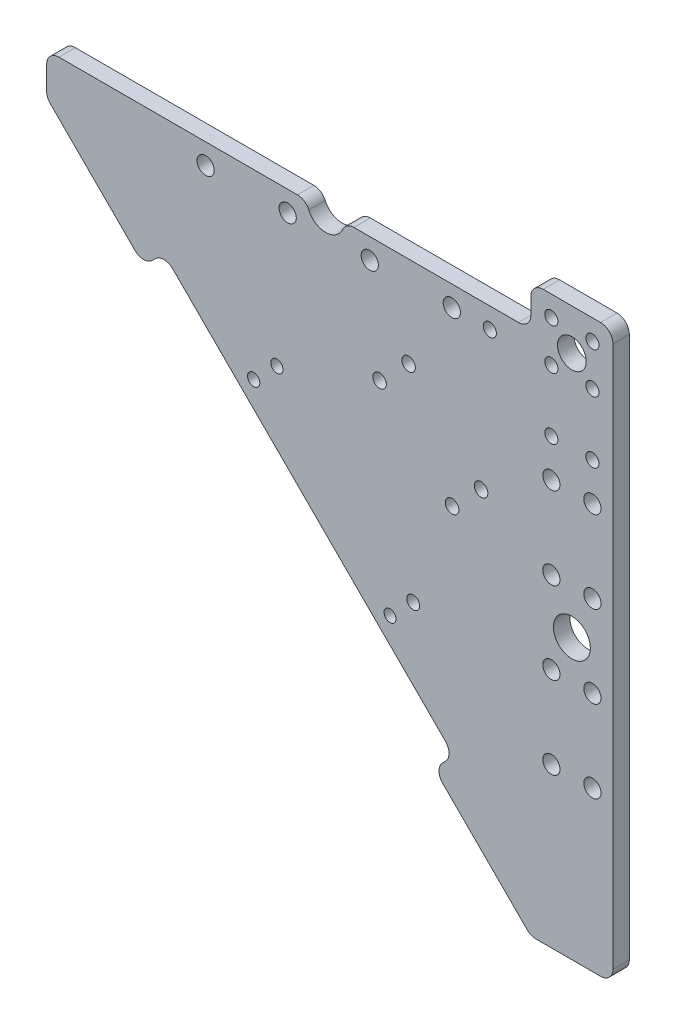
SolidWorks part; units mm, degrees
material "Thornel Mat VMA"
ref_plane "前视基准面" through (0, 0, 0) normal (0, 0, 1) x (1, 0, 0)
ref_plane "上视基准面" through (0, 0, 0) normal (0, 1, 0) x (1, 0, 0)
ref_plane "右视基准面" through (0, 0, 0) normal (1, 0, 0) x (0, 0, -1)
other "Configuration Table"
sketch "草图1" plane through (0, 0, 0) normal (0, 0, 1) x (1, 0, 0)
  line L0 (-128, -10) -> (-10, -128)
  line L5 (-10, 10) -> (10, 10)
  line L6 (-10, 10) -> (-10, -10)
  line L11 (-10, -10) -> (10, -10)
  line L12 (10, 10) -> (10, -10)
  line L13 (-10, 10) -> (10, -10) construction
  line L14 (-10, -10) -> (10, 10) construction
  line L15 (-10, -128) -> (10, -128)
  line L16 (-10, -128) -> (-10, -10)
  line L17 (-10, -10) -> (10, -10)
  line L18 (10, -128) -> (10, -10)
  line L19 (-10, -128) -> (10, -10) construction
  line L20 (-10, -10) -> (10, -128) construction
  line L21 (-128, 10) -> (-10, 10)
  line L22 (-128, 10) -> (-128, -10)
  line L23 (-128, -10) -> (-10, -10)
  line L24 (-10, 10) -> (-10, -10)
  line L25 (-128, 10) -> (-10, -10) construction
  line L26 (-128, -10) -> (-10, 10) construction
  circle A1 centre (-46.8744, -29.1967) radius 1.65 construction
  circle A2 centre (-29.1967, -46.8744) radius 1.65 construction
  circle A3 centre (-22.1256, -39.8033) radius 1.65 construction
  circle A4 centre (-39.8033, -22.1256) radius 1.65 construction
  circle A5 centre (-46.8744, -29.1967) radius 1.65
  circle A6 centre (-29.1967, -46.8744) radius 1.65
  circle A7 centre (-22.1256, -39.8033) radius 1.65
  circle A8 centre (-39.8033, -22.1256) radius 1.65
  circle A9 centre (-77.5485, -44.3145) radius 1.5 construction
  circle A10 centre (-77.5485, -44.3145) radius 1.5
  circle A11 centre (-44.3145, -77.5485) radius 1.4628 construction
  circle A12 centre (-38.6576, -71.8917) radius 1.5829 construction
  circle A13 centre (-71.8917, -38.6576) radius 1.5 construction
  circle A14 centre (-44.3145, -77.5485) radius 1.4628
  circle A15 centre (-38.6576, -71.8917) radius 1.5829
  circle A16 centre (-77.5485, -44.3145) radius 1.5
  circle A17 centre (-71.8917, -38.6576) radius 1.5
  point P0 (0, 0)
  point P6 (0, -69)
  point P7 (-69, 0)
  dimension "D1" = 20
  dimension "D2" = 20
  dimension "D3" = 118
  dimension "D4" = 118
extrude "凸台-拉伸1" add sketch "草图1" along normal blind 4 contours L22 L23 L6 L21 | L12 L5 L6 L11 | L15 L18 L11 L16 | L23 L0 L16
sketch "草图3" plane through (0, 0, 4) normal (0, 0, 1) x (1, 0, 0)
  line L1 (-5, 5) -> (5, 5) construction
  line L2 (-5, 5) -> (-5, -5) construction
  line L3 (-5, -5) -> (5, -5) construction
  line L4 (5, 5) -> (5, -5) construction
  line L5 (-5, 5) -> (5, -5) construction
  line L6 (-5, -5) -> (5, 5) construction
  circle A0 centre (0, 0) radius 3.5
  circle A1 centre (5, 5) radius 1.6
  circle A2 centre (-5, 5) radius 1.6
  circle A3 centre (-5, -5) radius 1.6
  circle A4 centre (5, -5) radius 1.6
  circle A5 centre (-20, -5) radius 1.6
  circle A6 centre (-5, -20) radius 1.6
  circle A7 centre (5, -20) radius 1.6
  circle A8 centre (5, 20) radius 1.6
  circle A9 centre (-5, 20) radius 1.6
  circle A10 centre (20, -5) radius 1.6
  circle A11 centre (20, 5) radius 1.6
  circle A12 centre (-20, 5) radius 1.6
  dimension "D1" = 10
  dimension "D5" = 3.2
  dimension "D10" = 20
  dimension "D11" = 20
  dimension "D13" = 3.2
  dimension "D15" = 3.2
  dimension "D2" = 10
  dimension "D3" = 2
  dimension "D4" = 2
  dimension "D6" = 2
  dimension "D7" = 2
  dimension "D8" = 2
  dimension "D9" = 2
extrude "切除-拉伸1" cut sketch "草图3" against normal blind 4
sketch "草图4" plane through (0, 0, 4) normal (0, 0, 1) x (1, 0, 0)
  line L1 (-128, 10) -> (10, 10) construction
  circle A0 centre (0, -60) radius 4.5
  circle A1 centre (-5, -29.2639) radius 2.1
  circle A2 centre (5, -29.2639) radius 2.1
  circle A3 centre (5, -49.2639) radius 2.1
  circle A4 centre (5, -69.2639) radius 2.1
  circle A5 centre (5, -89.2639) radius 2.1
  circle A6 centre (-5, -49.2639) radius 2.1
  circle A7 centre (-5, -69.2639) radius 2.1
  circle A8 centre (-5, -89.2639) radius 2.1
  circle A9 centre (-89.2639, -5) radius 2.1
  circle A10 centre (-69.2639, -5) radius 2.1
  circle A11 centre (-49.2639, -5) radius 2.1
  circle A12 centre (-89.2639, 5) radius 2.1
  circle A13 centre (-69.2639, 5) radius 2.1
  circle A14 centre (-49.2639, 5) radius 2.1
  circle A15 centre (-29.2639, 5) radius 2.1
  circle A16 centre (-29.2639, -5) radius 2.1
  circle A17 centre (-60, 0) radius 4.5
  dimension "D1" = 60
  dimension "D4" = 5
  dimension "D5" = 4.2
  dimension "D6" = 10
  dimension "D7" = 5
  dimension "D2" = 2
  dimension "D3" = 4
extrude "切除-拉伸2" cut sketch "草图4" against normal blind 4
sketch "草图10" plane through (0, 0, 4) normal (0, 0, 1) x (1, 0, 0)
  line L0 (10, 10) -> (-69, -69) construction
  line L1 (-128, -10) -> (-10, -128) construction
  line L2 (-45.8776, -28.1999) -> (-38.8065, -21.1289) construction
  line L3 (-45.8776, -28.1999) -> (-28.1999, -45.8776) construction
  line L4 (-38.8065, -21.1289) -> (-21.1289, -38.8065) construction
  line L5 (-28.1999, -45.8776) -> (-21.1289, -38.8065) construction
  line L6 (-45.8776, -28.1999) -> (-21.1289, -38.8065) construction
  line L7 (-38.8065, -21.1289) -> (-28.1999, -45.8776) construction
  line L8 (-72.5497, -42.4976) -> (-66.8928, -36.8408) construction
  line L9 (-72.5497, -42.4976) -> (-42.4976, -72.5497) construction
  line L10 (-66.8928, -36.8408) -> (-36.8408, -66.8928) construction
  line L11 (-42.4976, -72.5497) -> (-36.8408, -66.8928) construction
  line L12 (-72.5497, -42.4976) -> (-36.8408, -66.8928) construction
  line L13 (-66.8928, -36.8408) -> (-42.4976, -72.5497) construction
  circle A0 centre (-36.8408, -66.8928) radius 1.5
  circle A1 centre (-42.4976, -72.5497) radius 1.5
  circle A2 centre (-72.5497, -42.4976) radius 1.5
  circle A3 centre (-66.8928, -36.8408) radius 1.5
  circle A4 centre (-28.1999, -45.8776) radius 2
  circle A5 centre (-21.1289, -38.8065) radius 2
  circle A6 centre (-38.8065, -21.1289) radius 2
  circle A7 centre (-45.8776, -28.1999) radius 2
  point P6 (-33.5032, -33.5032)
  point P7 (-54.6952, -54.6952)
  dimension "D7" = 3
  dimension "D8" = 4
  dimension "D1" = 25
  dimension "D2" = 10
  dimension "D3" = 45.2
  dimension "D4" = 42.5
  dimension "D5" = 8
  dimension "D6" = 29.97
extrude "切除-拉伸6" [suppressed] cut sketch "草图10" against normal blind 4
sketch "草图11" plane through (0, 0, 4) normal (0, 0, 1) x (1, 0, 0)
  line L0 (0, 0) -> (-69, -69)
  line L1 (-128, -10) -> (-10, -128) construction
  line L2 (-99.4056, -28.6949) -> (-104.3553, -33.6447)
  line L3 (-99.4056, -28.6949) -> (-28.6949, -99.4056)
  line L4 (-104.3553, -33.6447) -> (-33.6447, -104.3553)
  line L5 (-28.6949, -99.4056) -> (-33.6447, -104.3553)
  line L6 (-99.4056, -28.6949) -> (-33.6447, -104.3553) construction
  line L7 (-104.3553, -33.6447) -> (-28.6949, -99.4056) construction
  point P6 (-66.5251, -66.5251)
  line M40 (-128, -10) -> (-10, -128)
  dimension "D1" = 7
  dimension "D2" = 100
extrude "切除-拉伸7" cut sketch "草图11" against normal blind 4 contours L3 L2 L0 M40 | L5 L3 L0 M40
sketch "草图12" plane through (0, 0, 4) normal (0, 0, 1) x (1, 0, 0)
  line L0 (-128, 10) -> (-10, 10)
  line L1 (-128, 10) -> (-128, 0)
  line L2 (-10, 10) -> (-10, 0)
  line L3 (-128, 0) -> (-10, 0)
  line L4 (-128, 10) -> (10, 10) construction
  dimension "D1" = 10
  dimension "D2" = 118
extrude "切除-拉伸8" cut sketch "草图12" against normal blind 4
sketch "草图13" plane through (0, 0, 4) normal (0, 0, 1) x (1, 0, 0)
  line L1 (-10, 25) -> (10, 25)
  line L2 (-10, 25) -> (-10, 10)
  line L3 (-10, 10) -> (10, 10)
  line L4 (10, 25) -> (10, 10)
  line L5 (-10, 25) -> (10, 10) construction
  line L6 (-10, 10) -> (10, 25) construction
  circle A0 centre (-5, 20) radius 1.6
  circle A1 centre (5, 20) radius 1.6
  point P0 (0, 17.5)
  dimension "D3" = 5
  dimension "D4" = 5
  dimension "D5" = 3.2
  dimension "D1" = 15
  dimension "D2" = 10
extrude "凸台-拉伸4" add sketch "草图13" against normal blind 4
fillet "圆角4" radius 3 13 edges at (-128, -10, 2) (-104.3553, -33.6447, 2) (-99.4056, -28.6949, 2) (-28.6949, -99.4056, 2) (-33.6447, -104.3553, 2) (-10, -128, 2) (10, -128, 2) (-10, 0, 2) (-55.5, 0, 2) (-64.5, 0, 2) (-128, 0, 2) (10, 25, 2) (-10, 25, 2)
sketch "草图14" plane through (0, 0, 0) normal (0, 0, -1) x (-1, 0, 0)
  line L0 (-7, 25) -> (7, 25) construction
  line L1 (-10, 40) -> (10, 40)
  line L2 (-10, 40) -> (-10, 10)
  line L3 (-10, 10) -> (10, 10)
  line L4 (10, 40) -> (10, 10)
  line L5 (-10, 40) -> (10, 10) construction
  line L6 (-10, 10) -> (10, 40) construction
  line L7 (10, 3) -> (10, 22) construction
  point P0 (0, 25)
  dimension "D1" = 15
extrude "切除-拉伸9" cut sketch "草图14" against normal through all
fillet "圆角5" radius 3 2 edges at (10, 10, 2) (-10, 10, 2)
